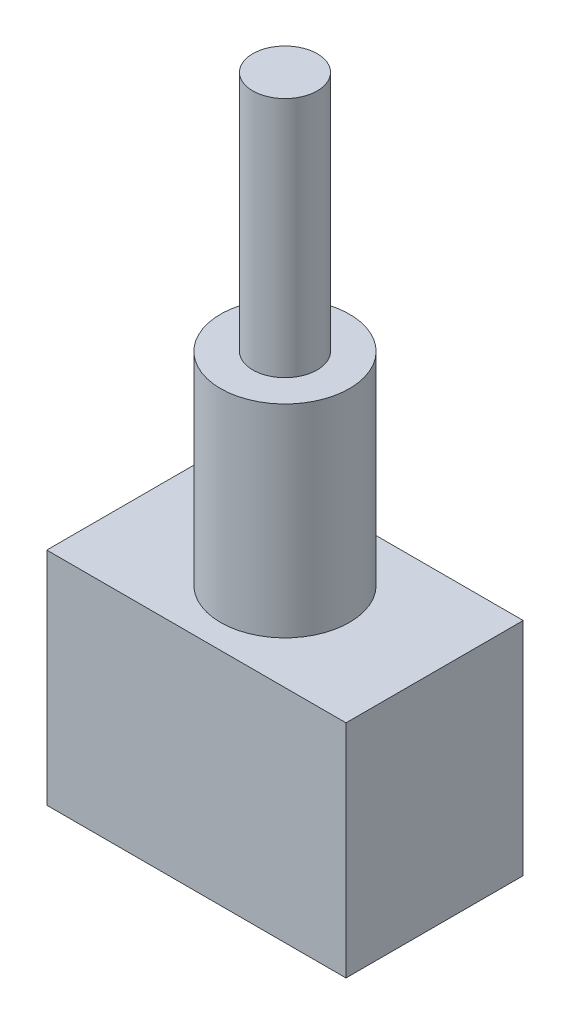
SolidWorks part; units mm, degrees
ref_plane "Front" through (0, 0, 0) normal (0, 0, 1) x (1, 0, 0)
ref_plane "Top" through (0, 0, 0) normal (0, 1, 0) x (1, 0, 0)
ref_plane "Right" through (0, 0, 0) normal (1, 0, 0) x (0, 0, -1)
sketch "Esboço2" plane through (0, 0, 0) normal (0, 0, 1) x (1, 0, 0)
  line L0 (0, 9.6) -> (13, 9.6)
  line L1 (13, 9.6) -> (13, 0)
  line L2 (13, 0) -> (0, 0)
  line L3 (0, 0) -> (0, 9.6)
  dimension "D1" = 13
  dimension "D2" = 9.6
extrude "Ressalto-extrusão1" add sketch "Esboço2" along normal blind 7.7
sketch "Esboço3" plane through (0, 9.6, 0) normal (0, 1, 0) x (1, 0, 0)
  line L0 (13, -7.7) -> (0, -7.7) construction
  circle A0 centre (6.5, -3.85) radius 2.8
  dimension "D1" = 5.6
  dimension "D2" = 3.85
  dimension "D3" = 6.5
extrude "Ressalto-extrusão2" add sketch "Esboço3" along normal blind 8.8
sketch "Esboço5" plane through (0, 18.4, 0) normal (0, 1, 0) x (1, 0, 0)
  line L0 (0, -7.7) -> (0, 0) construction
  line L1 (13, 0) -> (0, 0) construction
  circle A0 centre (6.5, -3.85) radius 1.4
  dimension "D1" = 2.8
  dimension "D2" = 6.5
  dimension "D3" = 3.85
extrude "Ressalto-extrusão3" add sketch "Esboço5" along normal blind 10.5
